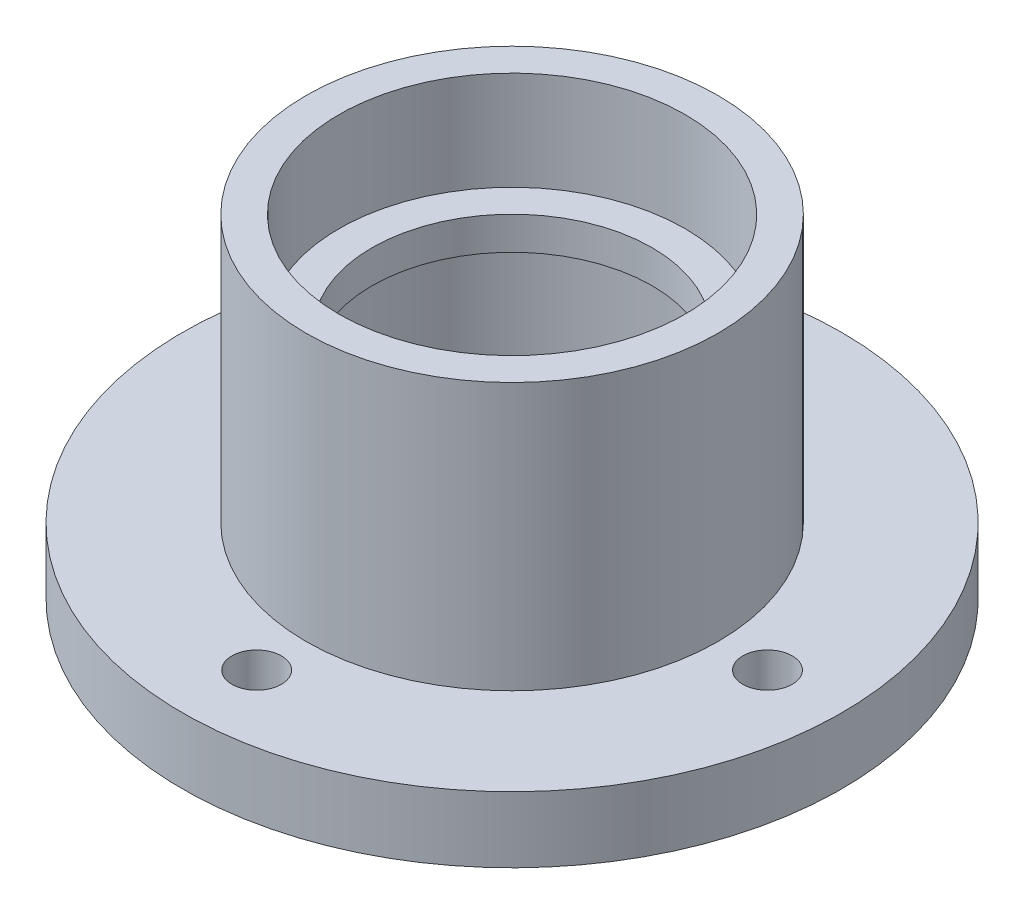
SolidWorks part; units mm, degrees
ref_plane "Front Plane" through (0, 0, 0) normal (0, 0, 1) x (1, 0, 0)
ref_plane "Top Plane" through (0, 0, 0) normal (0, 1, 0) x (1, 0, 0)
ref_plane "Right Plane" through (0, 0, 0) normal (1, 0, 0) x (0, 0, -1)
sketch "Sketch1" plane through (0, 0, 0) normal (0, 0, 1) x (1, 0, 0)
  line L0 (0, 0) -> (0, 23.3551) construction
  line L1 (-10.5, 20.2) -> (-10.5, 14.2)
  line L2 (-10.5, 14.2) -> (-8.5, 14.2)
  line L3 (-8.5, 14.2) -> (-8.5, 12.2)
  line L4 (-8.5, 12.2) -> (-10.5, 12.2)
  line L5 (-10.5, 12.2) -> (-10.5, 0)
  line L6 (-10.5, 0) -> (-20, 0)
  line L7 (-20, 0) -> (-20, 4)
  line L8 (-20, 4) -> (-12.5, 4)
  line L9 (-12.5, 4) -> (-12.5, 20.2)
  line L10 (-12.5, 20.2) -> (-10.5, 20.2)
  dimension "D1" = 21
  dimension "D2" = 6
  dimension "D3" = 2
  dimension "D4" = 12.2
  dimension "D5" = 40
  dimension "D6" = 2
  dimension "D7" = 4
  dimension "D8" = 17
revolve "Revolve1" add sketch "Sketch1" angle 360 about L0
sketch "Sketch2" plane through (0, 4, 0) normal (0, 1, 0) x (1, 0, 0)
  line L0 (0, 0) -> (0, 15.5) construction
  circle A0 centre (0, 15.5) radius 1.5
  circle A1 centre (15.5, 0) radius 1.5
  circle A2 centre (0, -15.5) radius 1.5
  circle A3 centre (-15.5, 0) radius 1.5
  point P12 (0, 0)
  dimension "D1" = 3
  dimension "D2" = 15.5
  dimension "D3" = 4
extrude "Cut-Extrude1" cut sketch "Sketch2" against normal through all
